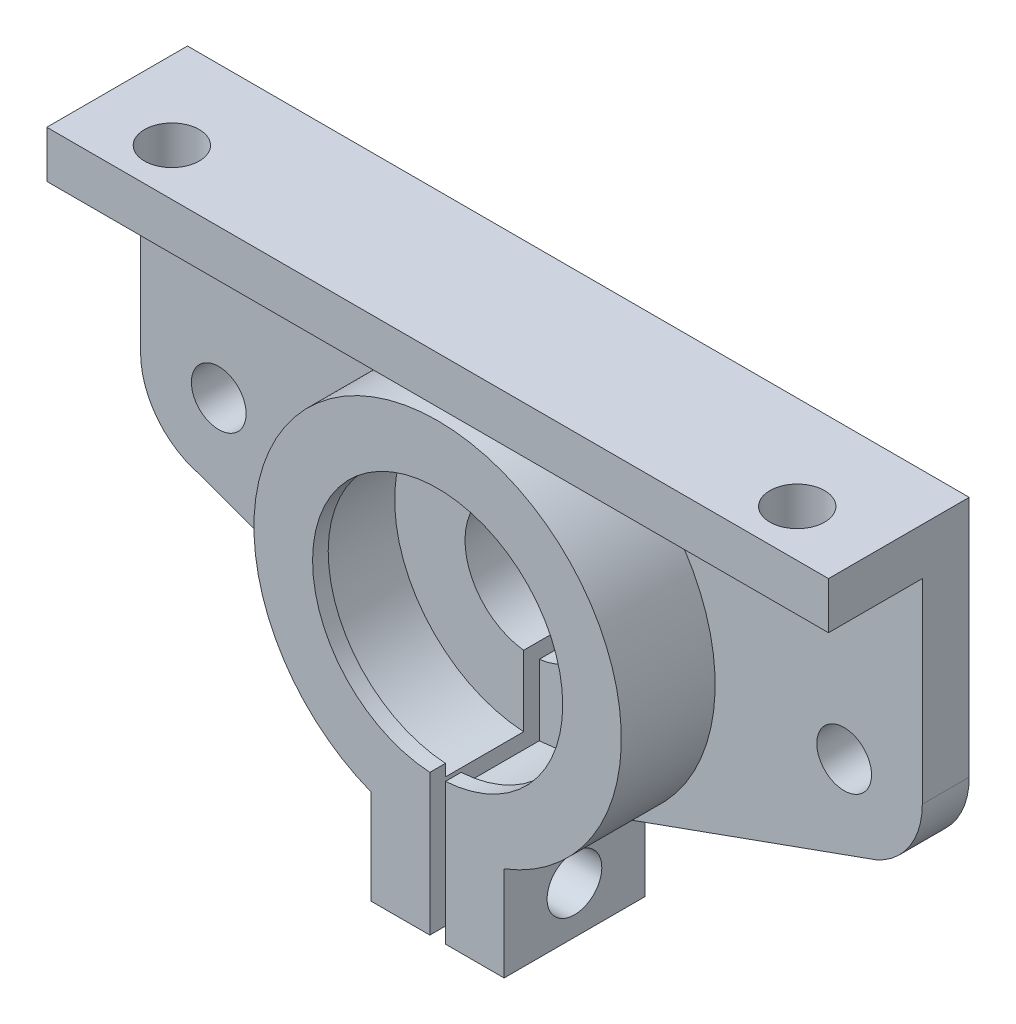
SolidWorks part; units mm, degrees
ref_plane "Front Plane" through (0, 0, 0) normal (0, 0, 1) x (1, 0, 0)
ref_plane "Top Plane" through (0, 0, 0) normal (0, 1, 0) x (1, 0, 0)
ref_plane "Right Plane" through (0, 0, 0) normal (1, 0, 0) x (0, 0, -1)
sketch "Sketch1" plane through (0, 0, 0) normal (0, 0, 1) x (1, 0, 0)
  line L0 (-40, 0) -> (40, 0) construction
  line L1 (-8.5, -21.9089) -> (-44.1949, -9.0776)
  line L2 (40, 0) -> (56.3363, 0) construction
  line L3 (0, 0) -> (0, 8.5) construction
  line L4 (-50, 0) -> (-50, 25)
  line L5 (40, -10.7872) -> (40, 0) construction
  line L6 (50, 0) -> (40, 0) construction
  line L7 (-50, 0) -> (-40, 0) construction
  line L8 (-40, -10.7872) -> (-40, 0) construction
  line L9 (50, 0) -> (50, 25)
  line L11 (-40, 0) -> (-56.3363, 0) construction
  line L13 (8.5, -21.9089) -> (44.1949, -9.0776)
  line L14 (-50, 25) -> (50, 25)
  line L18 (0, 0) -> (0, -34) construction
  line L19 (-8.5, -34) -> (8.5, -34)
  line L20 (-8.5, -34.8399) -> (-8.5, -21.9089)
  line L21 (8.5, -34) -> (8.5, -21.9089)
  circle A0 centre (0, 0) radius 8.5
  circle A1 centre (0, 0) radius 17.5 construction
  circle A3 centre (-40, 0) radius 3.5
  arc A4 (-50, 0) -> (-40, -10) centre (-40, 0) ccw
  arc A7 (-30, 0) -> (-50, 0) centre (-40, 0) ccw construction
  arc A8 (-40, -10) -> (-30, 0) centre (-40, 0) ccw construction
  arc A9 (40, -10) -> (30, 0) centre (40, 0) cw construction
  arc A10 (30, 0) -> (50, 0) centre (40, 0) cw construction
  arc A11 (50, 0) -> (40, -10) centre (40, 0) cw
  circle A12 centre (40, 0) radius 3.5
  arc A13 (0, -23.5) -> (8.5, -21.9089) centre (0, 0) ccw construction
  arc A14 (-23.5, 0) -> (-8.5, -21.9089) centre (0, 0) ccw construction
  arc A15 (8.5, -21.9089) -> (23.5, 0) centre (0, 0) ccw construction
  arc A16 (23.5, 0) -> (-23.5, 0) centre (0, 0) ccw construction
  arc A17 (-8.5, -21.9089) -> (0, -23.5) centre (0, 0) ccw construction
  point P7 (0, 0)
  point P33 (0, -34)
  dimension "D1" = 17
  dimension "D2" = 35
  dimension "D4" = 17
  dimension "D5" = 7
  dimension "D6" = 20
  dimension "D7" = 34
  dimension "D8" = 47
  dimension "D3" = 40
  dimension "D9" = 25
extrude "Boss-Extrude1" add sketch "Sketch1" along normal blind 6
sketch "Sketch2" plane through (0, 0, 6) normal (0, 0, 1) x (1, 0, 0)
  line L1 (0, 0) -> (0, -8.5) construction
  line L5 (0, 0) -> (0, -34) construction
  line L6 (-8.5, -34) -> (8.5, -34) construction
  line L7 (-8.5, -34) -> (8.5, -34)
  line L8 (8.5, -34) -> (8.5, -21.9089)
  line L9 (-8.5, -34) -> (-8.5, -21.9089)
  circle A0 centre (0, 0) radius 17.5
  arc A1 (8.5, -21.9089) -> (-8.5, -21.9089) centre (0, 0) ccw
  circle A3 centre (0, 0) radius 8.5 construction
  arc A4 (-8.5, -21.9089) -> (0, -23.5) centre (0, 0) ccw construction
  arc A6 (0, -23.5) -> (8.5, -21.9089) centre (0, 0) ccw construction
  point P14 (0, -34)
  dimension "D1" = 35
  dimension "D2" = 47
extrude "Boss-Extrude2" add sketch "Sketch2" along normal blind 12
sketch "Sketch4" plane through (0, 0, 0) normal (0, 1, 0) x (1, 0, 0)
  line L0 (-23.5, -18) -> (23.5, -18) construction
  line L1 (17.5, -18) -> (16, -18)
  line L2 (17.5, -18) -> (17.5, -16)
  line L3 (17.5, -16) -> (16, -16)
  line L4 (16, -18) -> (16, -16)
  dimension "D1" = 17.5
  dimension "D2" = 2
  dimension "D3" = 1.5
sweep "Sweep1" add profiles "Sketch4" path edge at (17.5, 0, 18)
sketch "Sketch5" plane through (0, 0, 0) normal (1, 0, 0) x (0, 0, -1)
  line L0 (-6, 0) -> (0, 0) construction
  line L2 (0, -34) -> (0, -21.9089) construction
  circle A0 centre (-9, -28) radius 3.5
  dimension "D3" = 7
  dimension "D1" = 28
  dimension "D2" = 9
extrude "Cut-Extrude1" cut sketch "Sketch5" against normal through all both and the other way through all
sketch "Sketch9" plane through (0, 0, 0) normal (1, 0, 0) x (0, 0, -1)
  line L0 (-6, 0) -> (-6, 25) construction
  line L1 (0, 25) -> (-18, 25)
  line L2 (0, 25) -> (0, 31)
  line L3 (0, 31) -> (-18, 31)
  line L4 (-18, 25) -> (-18, 31)
  dimension "D1" = 6
  dimension "D2" = 12
extrude "Boss-Extrude6" add sketch "Sketch9" along normal through all and the other way through all
sketch "Sketch10" plane through (0, 0, 0) normal (0, 0, 1) x (1, 0, 0)
  line L5 (-1, 0) -> (1, 0)
  line L6 (1, 0) -> (1, -34)
  line L7 (-8.5, -34) -> (8.5, -34) construction
  line L8 (-1, 0) -> (-1, -34)
  line L9 (-1, -34) -> (1, -34)
  point P6 (0, 0)
  dimension "D1" = 1
extrude "Cut-Extrude10" cut sketch "Sketch10" against normal through all and the other way through all
sketch "Sketch11" plane through (0, 25, 0) normal (0, -1, 0) x (1, 0, 0)
  line L0 (0, 0) -> (0, 12) construction
  line L1 (-40, 12) -> (40, 12) construction
  line L2 (50, 18) -> (-50, 18) construction
  circle A0 centre (-40, 12) radius 3.5
  circle A1 centre (40, 12) radius 3.5
  point P7 (0, 12)
  dimension "D2" = 7
  dimension "D1" = 80
  dimension "D3" = 6
extrude "Cut-Extrude11" cut sketch "Sketch11" against normal through all
